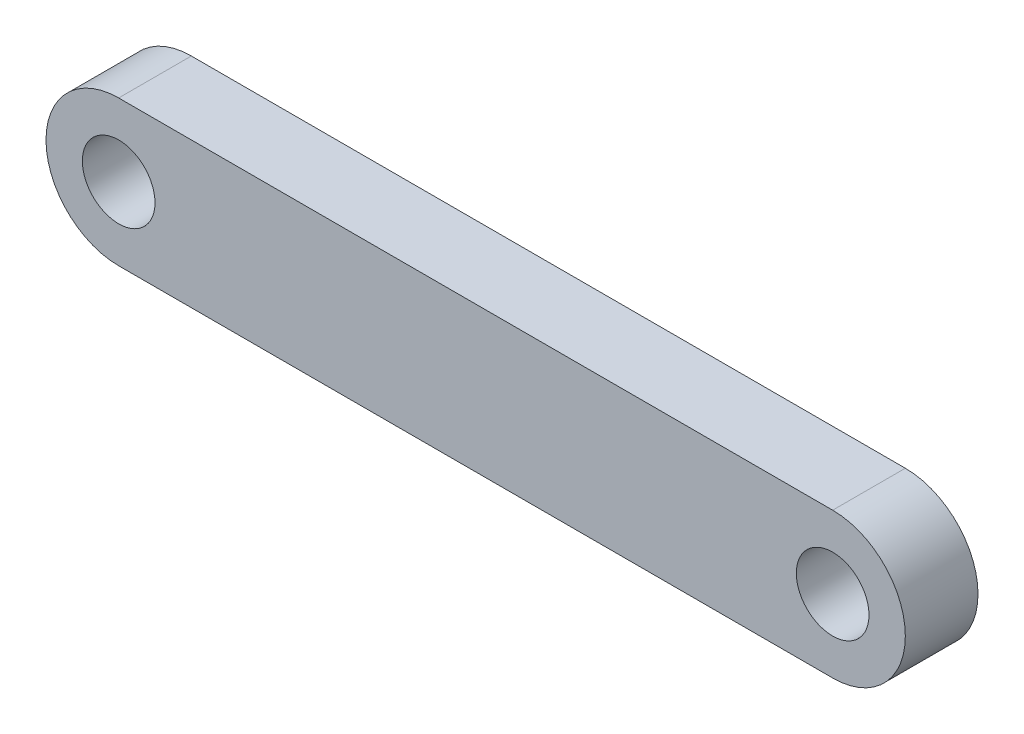
SolidWorks part; units mm, degrees
ref_plane "Front Plane" through (0, 0, 0) normal (0, 0, 1) x (1, 0, 0)
ref_plane "Top Plane" through (0, 0, 0) normal (0, 1, 0) x (1, 0, 0)
ref_plane "Right Plane" through (0, 0, 0) normal (1, 0, 0) x (0, 0, -1)
sketch "Sketch1" plane through (0, 0, 0) normal (0, 0, 1) x (1, 0, 0)
  line L0 (0, 0) -> (19.65, 0) construction
  line L1 (0, 2) -> (19.65, 2)
  line L2 (0, -2) -> (19.65, -2)
  arc A0 (0, 2) -> (0, -2) centre (0, 0) ccw
  arc A1 (19.65, -2) -> (19.65, 2) centre (19.65, 0) ccw
  circle A2 centre (0, 0) radius 1
  circle A3 centre (19.65, 0) radius 1
  point P3 (9.825, 0)
  dimension "D1" = 2
  dimension "D3" = 2
  dimension "D2" = 19.65
extrude "Boss-Extrude1" add sketch "Sketch1" along normal blind 2
